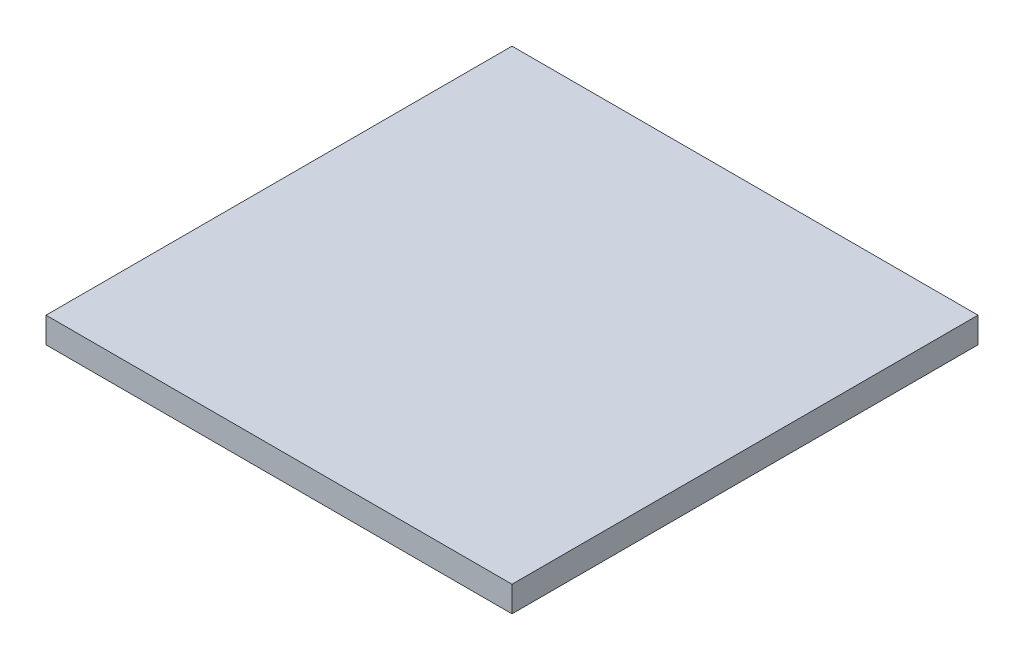
SolidWorks part; units mm, degrees
material "Glass"
ref_plane "Front Plane" through (0, 0, 0) normal (0, 0, 1) x (1, 0, 0)
ref_plane "Top Plane" through (0, 0, 0) normal (0, 1, 0) x (1, 0, 0)
ref_plane "Right Plane" through (0, 0, 0) normal (1, 0, 0) x (0, 0, -1)
sketch "Sketch1" plane through (0, 0, 0) normal (0, 1, 0) x (1, 0, 0)
  line L1 (-25.4, 25.4) -> (25.4, 25.4)
  line L2 (-25.4, 25.4) -> (-25.4, -25.4)
  line L3 (-25.4, -25.4) -> (25.4, -25.4)
  line L4 (25.4, 25.4) -> (25.4, -25.4)
  line L5 (0, -25.4) -> (0, 25.4) construction
  line L6 (-25.4, 0) -> (25.4, 0) construction
  point P0 (0, 0)
  dimension "D1" = 50.8
extrude "Boss-Extrude1" add sketch "Sketch1" along normal blind 2.8
